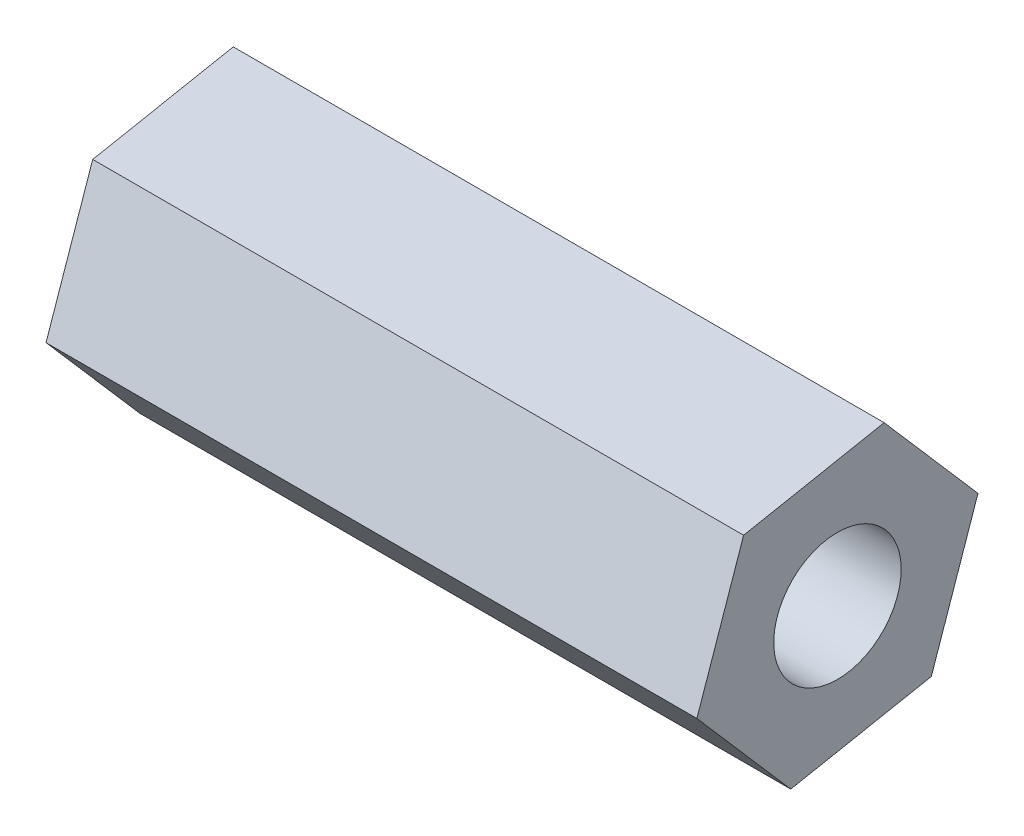
SolidWorks part; units mm, degrees
material "3003 Alloy"
ref_plane "Front Plane" through (0, 0, 0) normal (0, 0, 1) x (1, 0, 0)
ref_plane "Top Plane" through (0, 0, 0) normal (0, 1, 0) x (1, 0, 0)
ref_plane "Right Plane" through (0, 0, 0) normal (1, 0, 0) x (0, 0, -1)
sketch "Sketch1" plane through (0, 0, 0) normal (1, 0, 0) x (0, 0, -1)
  line L1 (-4.8062, 5.5375) -> (-7.1987, -1.3935)
  line L2 (-7.1987, -1.3935) -> (-2.3926, -6.931)
  line L3 (-2.3926, -6.931) -> (4.8062, -5.5375)
  line L4 (4.8062, -5.5375) -> (7.1987, 1.3935)
  line L5 (7.1987, 1.3935) -> (2.3926, 6.931)
  line L6 (2.3926, 6.931) -> (-4.8062, 5.5375)
  circle A0 centre (0, 0) radius 6.35 construction
  dimension "D1" = 12.7
extrude "Boss-Extrude1" add sketch "Sketch1" along normal blind 33.3375
sketch "Sketch2" plane through (33.3375, 0, 0) normal (1, 0, 0) x (0, 0, -1)
  circle A0 centre (0, 0) radius 3.2639
  dimension "D1" = 6.5278
extrude "Cut-Extrude1" cut sketch "Sketch2" against normal blind 38.1
